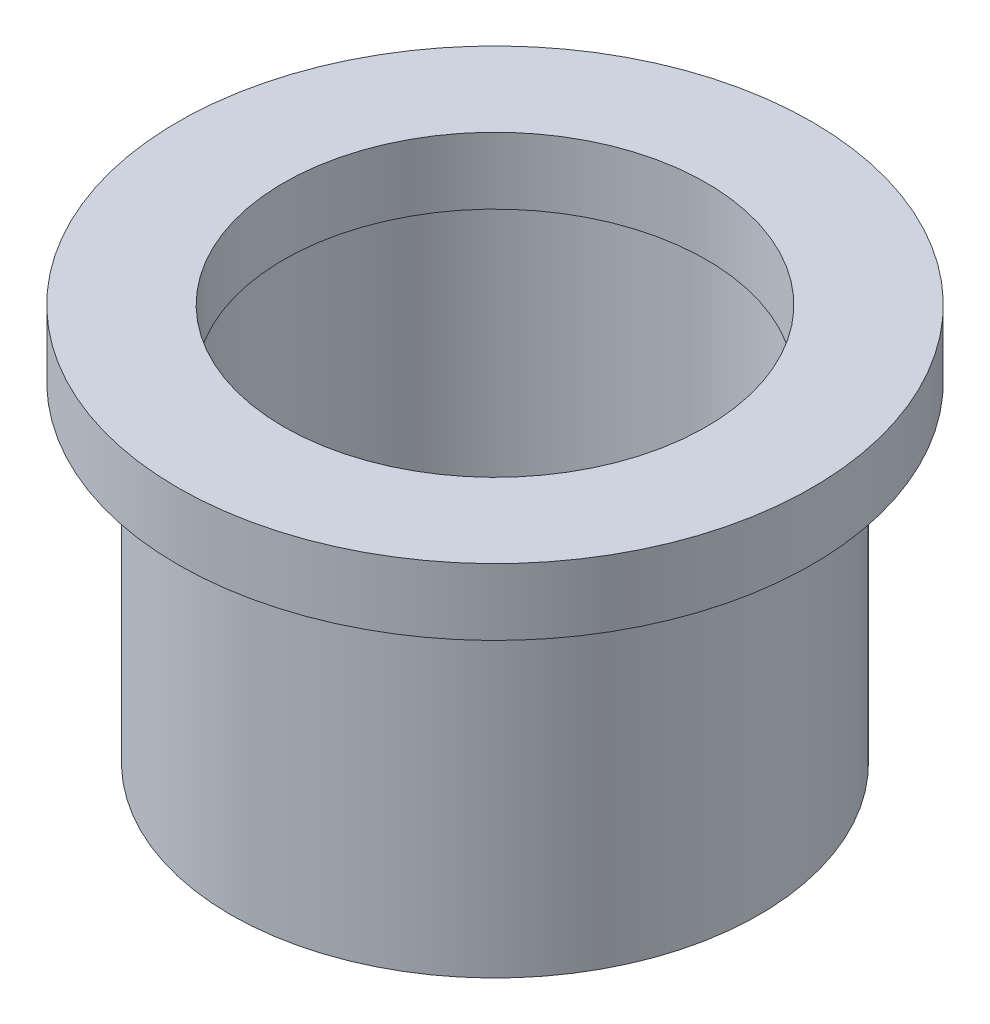
SolidWorks part; units mm, degrees
ref_plane "Front Plane" through (0, 0, 0) normal (0, 0, 1) x (1, 0, 0)
ref_plane "Top Plane" through (0, 0, 0) normal (0, 1, 0) x (1, 0, 0)
ref_plane "Right Plane" through (0, 0, 0) normal (1, 0, 0) x (0, 0, -1)
sketch "Sketch1" plane through (0, 0, 0) normal (0, 0, 1) x (1, 0, 0)
  line L0 (3.175, -3.1439) -> (3.175, -4.1439)
  line L1 (3.175, -4.1439) -> (3.2188, -4.1439)
  line L2 (3.2188, -4.1439) -> (3.2188, -9.097)
  line L3 (3.2188, -9.097) -> (3.9688, -9.097)
  line L4 (3.9688, -9.097) -> (3.9688, -4.1439)
  line L5 (3.9688, -4.1439) -> (4.7625, -4.1439)
  line L6 (4.7625, -4.1439) -> (4.7625, -3.1439)
  line L7 (4.7625, -3.1439) -> (3.175, -3.1439)
  line L8 (0, 0) -> (0, -17.2894) construction
  dimension "D1" = 4.7625
  dimension "D2" = 6.35
  dimension "D3" = 7.9375
  dimension "D4" = 5.9531
  dimension "D5" = 1
  dimension "D6" = 0.75
revolve "Revolve1" add sketch "Sketch1" angle 360 about L8
